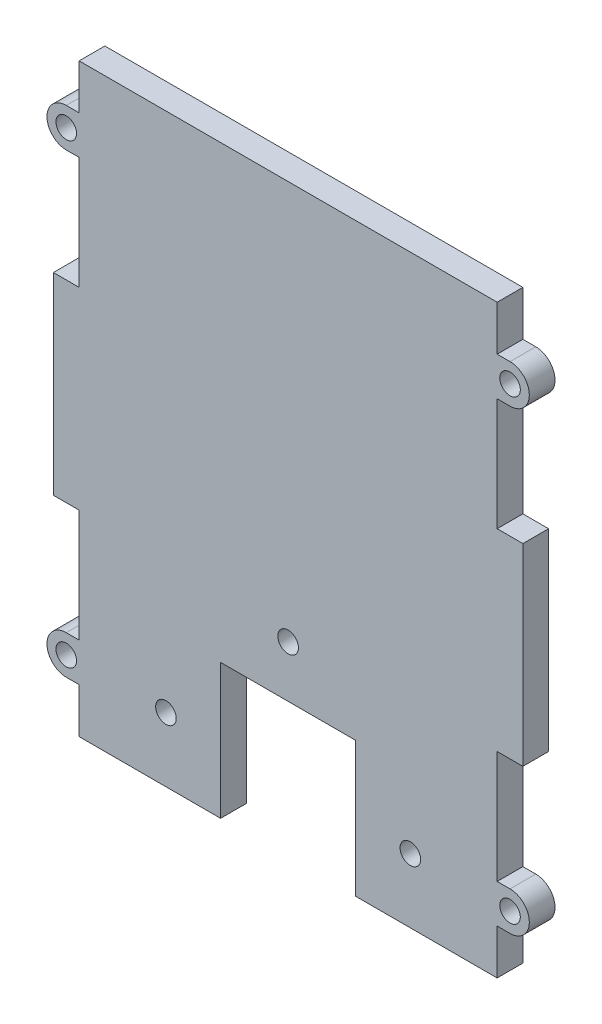
SolidWorks part; units mm, degrees
ref_plane "Front Plane" through (0, 0, 0) normal (0, 0, 1) x (1, 0, 0)
ref_plane "Top Plane" through (0, 0, 0) normal (0, 1, 0) x (1, 0, 0)
ref_plane "Right Plane" through (0, 0, 0) normal (1, 0, 0) x (0, 0, -1)
sketch "Sketch1" plane through (0, 0, 0) normal (0, 0, 1) x (1, 0, 0)
  line L0 (-10.5, -45.5) -> (-10.5, -24.5)
  line L1 (-32.5, 45.5) -> (32.5, 45.5)
  line L2 (-32.5, 45.5) -> (-32.5, -45.5)
  line L3 (-32.5, -45.5) -> (-10.5, -45.5)
  line L4 (32.5, 45.5) -> (32.5, -45.5)
  line L5 (-32.5, 45.5) -> (32.5, -45.5) construction
  line L6 (-32.5, -45.5) -> (32.5, 45.5) construction
  line L7 (-10.5, -24.5) -> (10.5, -24.5)
  line L8 (10.5, -24.5) -> (10.5, -45.5)
  line L9 (10.5, -45.5) -> (32.5, -45.5)
  point P1 (0, 0)
  point P10 (0, -24.5)
  dimension "D1" = 21
  dimension "D2" = 21
  dimension "D3" = 91
  dimension "D4" = 65
extrude "Boss-Extrude1" add sketch "Sketch1" along normal blind 4
sketch "Sketch2" plane through (0, 0, 0) normal (0, 0, -1) x (-1, 0, 0)
  circle A0 centre (19, -35.5) radius 1.6
  circle A1 centre (0, -16.5) radius 1.6
  circle A2 centre (-19, -35.5) radius 1.6
extrude "Cut-Extrude1" cut sketch "Sketch2" against normal through all
sketch "Sketch3" plane through (0, 0, 0) normal (0, 0, -1) x (-1, 0, 0)
  line L0 (-32.5, 0) -> (32.5, 0) construction
  line L1 (32.5, 45.5) -> (32.5, -45.5) construction
  line L2 (-32.5, -45.5) -> (-32.5, 45.5) construction
  line L3 (-32.5, 45.5) -> (32.5, 45.5) construction
  line L4 (32.5, 38.5) -> (34.5, 38.5)
  line L5 (34.5, 32.5) -> (32.5, 32.5)
  line L7 (34.5, -32.5) -> (32.5, -32.5)
  line L8 (32.5, -38.5) -> (34.5, -38.5)
  line L9 (0, 45.5) -> (0, -45.5) construction
  line L10 (-32.5, -38.5) -> (-34.5, -38.5)
  line L11 (-34.5, -32.5) -> (-32.5, -32.5)
  line L12 (-34.5, 32.5) -> (-32.5, 32.5)
  line L13 (-32.5, 38.5) -> (-34.5, 38.5)
  circle A1 centre (34.5, 35.5) radius 1.6
  arc A3 (34.5, 38.5) -> (34.5, 32.5) centre (34.5, 35.5) cw
  arc A4 (34.5, -38.5) -> (34.5, -32.5) centre (34.5, -35.5) ccw
  circle A5 centre (34.5, -35.5) radius 1.6
  circle A6 centre (-34.5, -35.5) radius 1.6
  arc A7 (-34.5, -38.5) -> (-34.5, -32.5) centre (-34.5, -35.5) cw
  arc A8 (-34.5, 38.5) -> (-34.5, 32.5) centre (-34.5, 35.5) ccw
  circle A9 centre (-34.5, 35.5) radius 1.6
  line M12 (32.5, -45.5) -> (32.5, 45.5)
  line M14 (-32.5, 45.5) -> (-32.5, -45.5)
  dimension "D1" = 3.2
  dimension "D2" = 10
  dimension "D3" = 2
  dimension "D4" = 3
extrude "Boss-Extrude3" add sketch "Sketch3" against normal up to surface (4 mm away) contours A3 L4 A1 L5 M12 | A5 L8 A4 L7 M12 | A7 L10 A6 L11 M14 | A9 L13 A8 L12 M14 up to face at (-20.6, -35.5, 4)
sketch "Sketch4" plane through (0, 0, 0) normal (0, 0, -1) x (-1, 0, 0)
  line L0 (32.5, 32.5) -> (32.5, -32.5) construction
  line L1 (32.5, -15) -> (36.5, -15)
  line L2 (32.5, -15) -> (32.5, 15)
  line L3 (32.5, 15) -> (36.5, 15)
  line L4 (36.5, -15) -> (36.5, 15)
  line L5 (0, 45.5) -> (0, -24.5) construction
  line L6 (-32.5, 45.5) -> (32.5, 45.5) construction
  line L7 (10.5, -24.5) -> (-10.5, -24.5) construction
  line L8 (-36.5, -15) -> (-36.5, 15)
  line L9 (-32.5, 15) -> (-36.5, 15)
  line L10 (-32.5, -15) -> (-32.5, 15)
  line L11 (-32.5, -15) -> (-36.5, -15)
  point P6 (32.5, 0)
  dimension "D1" = 4
  dimension "D2" = 30
extrude "Boss-Extrude4" add sketch "Sketch4" against normal blind 4
